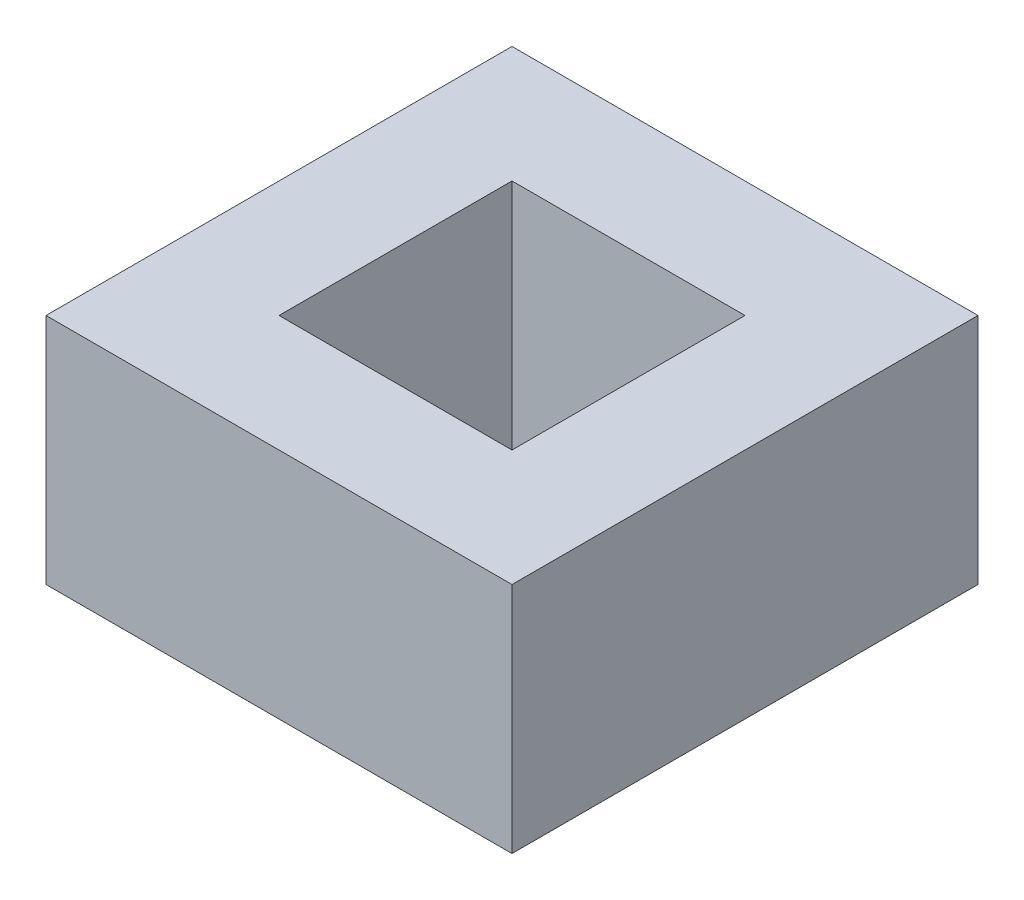
SolidWorks part; units mm, degrees
ref_plane "前视基准面" through (0, 0, 0) normal (0, 0, 1) x (1, 0, 0)
ref_plane "上视基准面" through (0, 0, 0) normal (0, 1, 0) x (1, 0, 0)
ref_plane "右视基准面" through (0, 0, 0) normal (1, 0, 0) x (0, 0, -1)
other "Configuration Table"
sketch "草图1" plane through (0, 0, 0) normal (0, 1, 0) x (1, 0, 0)
  line L0 (0, 0) -> (10, 0)
  line L1 (10, 0) -> (10, 10)
  line L2 (10, 10) -> (0, 10)
  line L3 (0, 10) -> (0, 0)
  line L4 (15, 15) -> (-5, 15)
  line L5 (-5, 15) -> (-5, -5)
  line L6 (-5, -5) -> (15, -5)
  line L7 (15, -5) -> (15, 15)
  dimension "D1" = 5
extrude "凸台-拉伸1" add sketch "草图1" along normal blind 10
